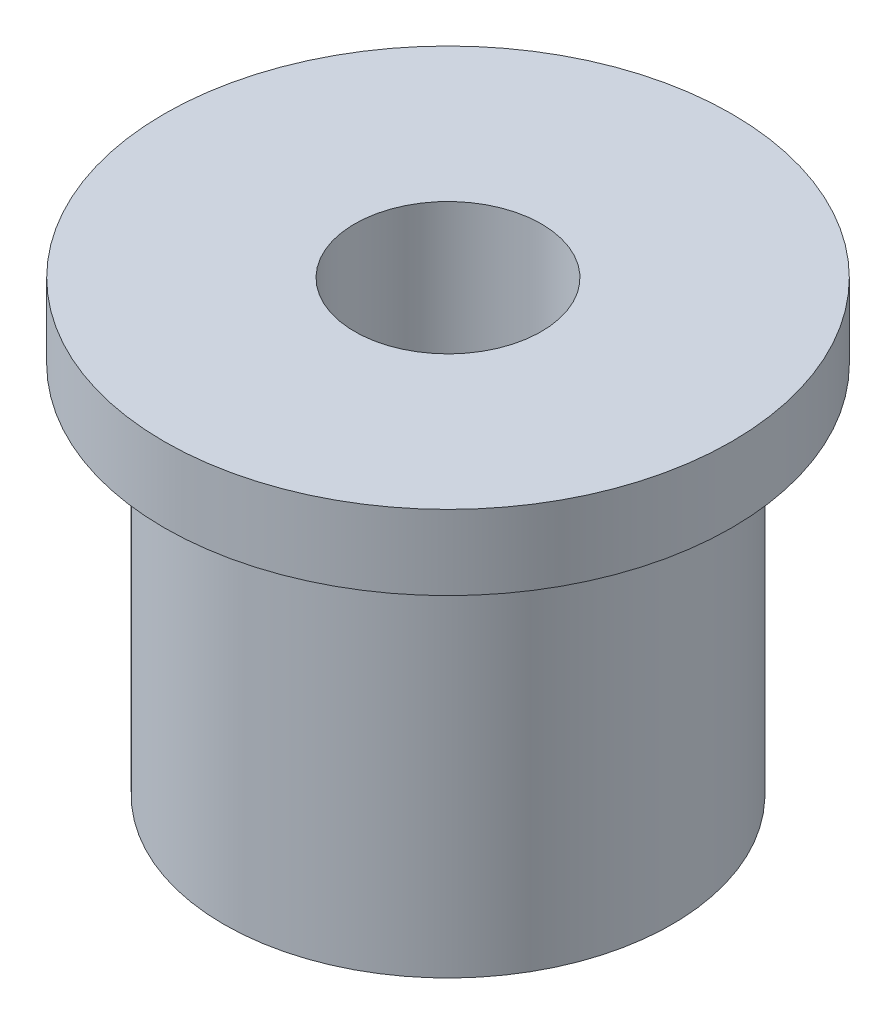
SolidWorks part; units mm, degrees
ref_plane "Front Plane" through (0, 0, 0) normal (0, 0, 1) x (1, 0, 0)
ref_plane "Top Plane" through (0, 0, 0) normal (0, 1, 0) x (1, 0, 0)
ref_plane "Right Plane" through (0, 0, 0) normal (1, 0, 0) x (0, 0, -1)
sketch "Sketch1" plane through (0, 0, 0) normal (1, 0, 0) x (0, 0, -1)
  line L0 (0, 0) -> (0, 12.3422) construction
  line L1 (1.25, 0) -> (1.25, 6)
  line L2 (1.25, 6) -> (3.8, 6)
  line L3 (3.8, 6) -> (3.8, 5)
  line L4 (3.8, 5) -> (3, 5)
  line L5 (3, 5) -> (3, 0)
  line L6 (3, 0) -> (1.25, 0)
  dimension "D1" = 1
  dimension "D2" = 5
  dimension "D3" = 1.25
  dimension "D4" = 3
  dimension "D5" = 3.8
revolve "Revolve1" add sketch "Sketch1" angle 360 about L0
